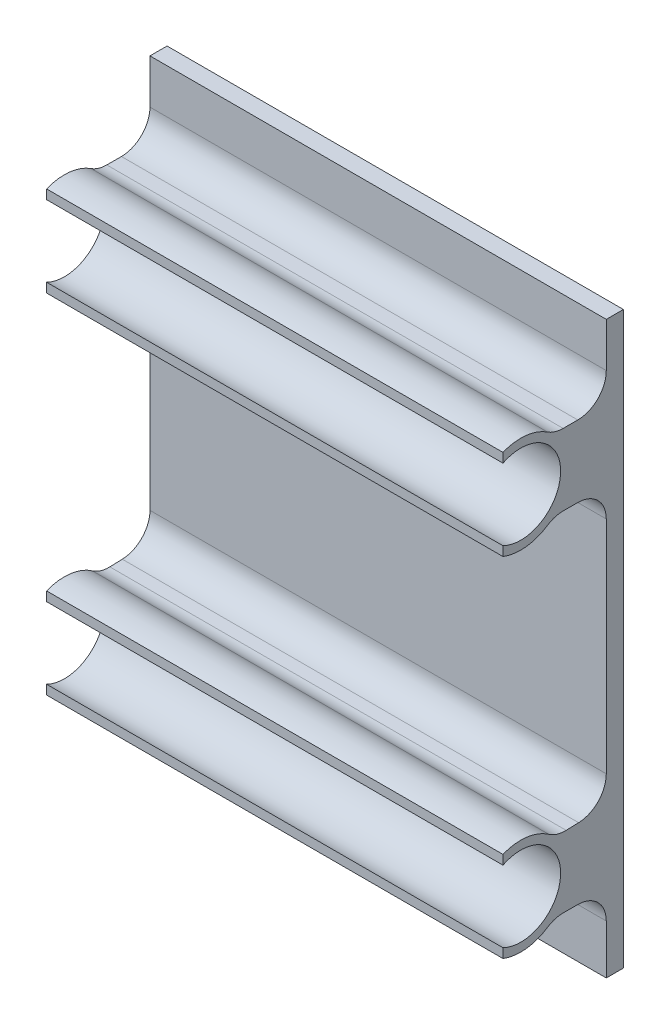
SolidWorks part; units mm, degrees
ref_plane "Front Plane" through (0, 0, 0) normal (0, 0, 1) x (1, 0, 0)
ref_plane "Top Plane" through (0, 0, 0) normal (0, 1, 0) x (1, 0, 0)
ref_plane "Right Plane" through (0, 0, 0) normal (1, 0, 0) x (0, 0, -1)
sketch "Sketch1" plane through (0, 0, 0) normal (0, 0, 1) x (1, 0, 0)
  line L0 (0, 0) -> (82.8306, 0) construction
  line L1 (0, 0) -> (0, 99.0276) construction
  line L2 (-21.5633, 58.7673) -> (58.4367, 58.7673)
  line L3 (58.4367, 58.7673) -> (58.4367, -41.2327)
  line L4 (58.4367, -41.2327) -> (-21.5633, -41.2327)
  line L5 (-21.5633, -41.2327) -> (-21.5633, 58.7673)
  dimension "D1" = 100
  dimension "D2" = 80
extrude "Boss-Extrude1" add sketch "Sketch1" along normal blind 3
sketch "Sketch3" plane through (58.4367, 0, 0) normal (1, 0, 0) x (0, 0, -1)
  line L0 (-3, -41.2327) -> (-3, 58.7673) construction
  line L1 (-1.8372, 45.9913) -> (-12.2579, 45.9913)
  line L2 (-21.1179, 47.6316) -> (-21.1179, 45.9913)
  line L3 (-21.1179, -13.402) -> (-21.1179, -15.0422)
  line L4 (-21.1179, -27.5767) -> (-21.1179, -29.217)
  line L5 (-21.1179, 33.4568) -> (-21.1179, 31.8166)
  line L6 (-1.8372, 45.9913) -> (-1.8372, 33.4568)
  line L7 (-1.8372, 33.4568) -> (-12.2579, 33.4568)
  line L8 (-1.8372, -15.0422) -> (-1.8372, -27.5767)
  line L9 (-1.8372, -27.5767) -> (-12.2579, -27.5767)
  line L10 (-1.8372, -15.0422) -> (-11.9367, -15.3524)
  arc A0 (-21.1179, 33.4568) -> (-21.1179, 45.9913) centre (-18, 39.7241) ccw
  arc A1 (-21.1179, -27.5767) -> (-21.1179, -15.0422) centre (-18, -21.3095) ccw
  arc A2 (-21.1179, 31.8166) -> (-12.2579, 33.4568) centre (-18, 39.7241) ccw
  arc A3 (-21.1179, -29.217) -> (-12.2579, -27.5767) centre (-18, -21.3095) ccw
  arc A4 (-11.9367, -15.3524) -> (-21.1179, -13.402) centre (-18, -21.3095) ccw
  arc A5 (-12.2579, 45.9913) -> (-21.1179, 47.6316) centre (-18, 39.7241) ccw
  point P1 (-9.0323, -20.62)
  dimension "D3" = 14
  dimension "D4" = 14
  dimension "D1" = 17
  dimension "D2" = 17
  dimension "D6" = 15
  dimension "D5" = 15
extrude "Boss-Extrude3" add sketch "Sketch3" against normal blind 80
fillet "Fillet1" radius 5 4 edges at (18.4367, -27.5767, 12.2579) (18.4367, -15.3524, 11.9367) (18.4367, 33.4568, 12.2579) (18.4367, 45.9913, 12.2579)
fillet "Fillet2" radius 5 4 edges at (18.4367, -15.0779, 3) (18.4367, -27.5767, 3) (18.4367, 33.4568, 3) (18.4367, 45.9913, 3)
